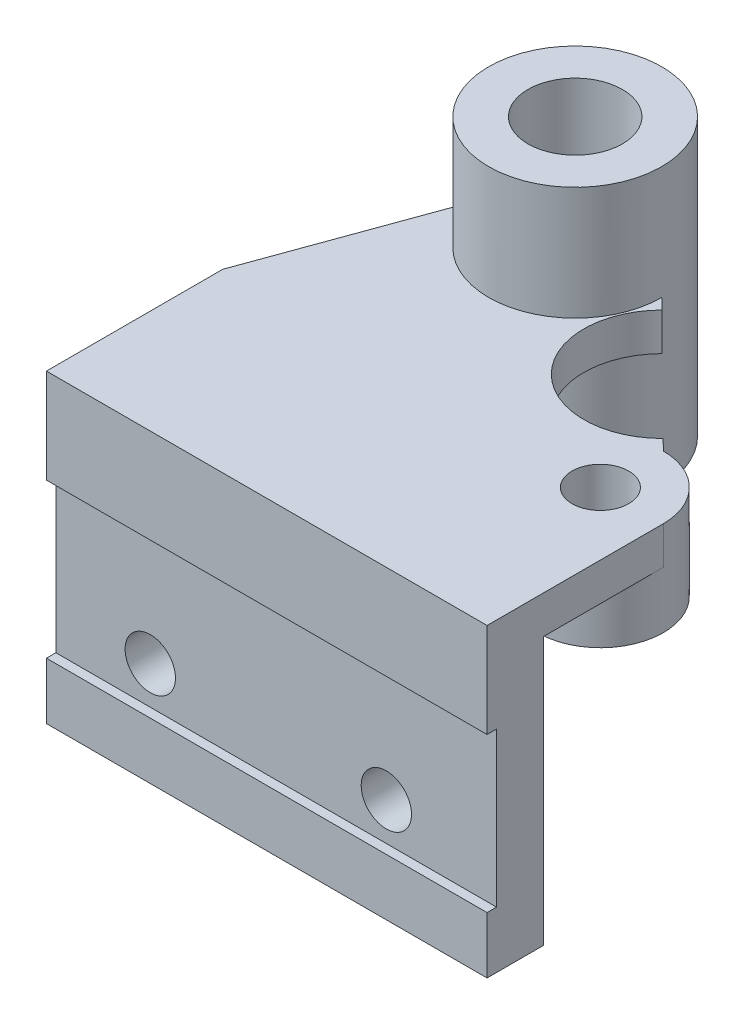
SolidWorks part; units mm, degrees
ref_plane "Front Plane" through (0, 0, 0) normal (0, 0, 1) x (1, 0, 0)
ref_plane "Top Plane" through (0, 0, 0) normal (0, 1, 0) x (1, 0, 0)
ref_plane "Right Plane" through (0, 0, 0) normal (1, 0, 0) x (0, 0, -1)
sketch "Sketch1" plane through (0, 0, 0) normal (0, 0, 1) x (1, 0, 0)
  line L1 (0, 0) -> (140, 0)
  line L2 (0, 0) -> (0, -85)
  line L3 (0, -85) -> (140, -85)
  line L4 (140, 0) -> (140, -85)
  dimension "D1" = 140
  dimension "D2" = 85
extrude "Boss-Extrude1" add sketch "Sketch1" along normal blind 18
sketch "Sketch2" plane through (140, 0, 0) normal (1, 0, 0) x (0, 0, -1)
  line L0 (-18, -85) -> (-18, 0) construction
  line L1 (-18, -18) -> (-15, -18)
  line L2 (-18, -18) -> (-18, -67)
  line L3 (-18, -67) -> (-15, -67)
  line L4 (-15, -18) -> (-15, -67)
  line L5 (-18, 0) -> (0, 0) construction
  dimension "D1" = 18
  dimension "D2" = 3
  dimension "D3" = 18
extrude "Cut-Extrude1" cut sketch "Sketch2" against normal blind 220
sketch "Sketch3" plane through (0, 0, 0) normal (0, 0, -1) x (-1, 0, 0)
  line L0 (-140, -85) -> (-140, 0) construction
  line L1 (0, -85) -> (-140, -85) construction
  line L2 (0, 0) -> (0, -85) construction
  circle A0 centre (-105, -55) radius 8
  circle A1 centre (-30, -55) radius 8
  dimension "D1" = 16
  dimension "D2" = 16
  dimension "D3" = 35
  dimension "D4" = 30
  dimension "D5" = 30
  dimension "D6" = 30
extrude "Cut-Extrude4" cut sketch "Sketch3" against normal blind 30
sketch "Sketch5" plane through (140, 0, 0) normal (1, 0, 0) x (0, 0, -1)
  line L0 (-18, 0) -> (0, 0) construction
  line L1 (-18, 0) -> (38, 0)
  line L2 (-18, 0) -> (-18, 12)
  line L3 (-18, 12) -> (38, 12)
  line L4 (38, 0) -> (38, 12)
  dimension "D1" = 12
  dimension "D2" = 56
extrude "Boss-Extrude2" add sketch "Sketch5" against normal blind 140
sketch "Sketch7" plane through (0, 0, 0) normal (0, -1, 0) x (1, 0, 0)
  line L0 (0, 0) -> (140, 0) construction
  line L2 (140, 0) -> (140, -38) construction
  circle A0 centre (120, -38) radius 20
  point P6 (140, -19)
  dimension "D2" = 40
  dimension "D1" = 38
  dimension "D3" = 20
extrude "Boss-Extrude3" add sketch "Sketch7" against normal blind 12 and the other way blind 18 from offset 0
sketch "Sketch8" plane through (0, -18, 0) normal (0, -1, 0) x (-1, 0, 0)
  line L0 (-120, 18) -> (-120, 50018) construction
  line L1 (-140, 38) -> (49860, 38) construction
  arc A0 (-140, 38) -> (-100, 38) centre (-120, 38) ccw construction
  circle A3 centre (-120, 38) radius 9
  point P5 (-120, 18)
  point P11 (-120, 38)
  dimension "D1" = 18
extrude "Cut-Extrude5" cut sketch "Sketch8" against normal blind 50
sketch "Sketch10" plane through (0, 0, 0) normal (0, -1, 0) x (1, 0, 0)
  line L0 (0, 0) -> (140, 0) construction
  line L1 (0, 0) -> (0, -38) construction
  line L2 (0, -38) -> (22.5, -100)
  line L3 (77.5, -100) -> (120, -58)
  line L4 (0, -38) -> (100, -38)
  arc A0 (77.5, -100) -> (22.5, -100) centre (50, -100) ccw
  circle A1 centre (120, -38) radius 20 construction
  arc A2 (100, -38) -> (120, -58) centre (120, -38) ccw
  dimension "D1" = 55
  dimension "D2" = 100
  dimension "D3" = 50
extrude "Boss-Extrude4" add sketch "Sketch10" against normal blind 12
sketch "Sketch11" plane through (0, 12, 0) normal (0, 1, 0) x (1, 0, 0)
  line L0 (50, 72.5) -> (50, 100) construction
  arc A0 (22.5, 100) -> (77.5, 100) centre (50, 100) ccw construction
  circle A1 centre (50, 100) radius 27.5
extrude "Boss-Extrude6" add sketch "Sketch11" along normal blind 36 and the other way blind 52
sketch "Sketch12" plane through (0, -40, 0) normal (0, -1, 0) x (1, 0, 0)
  line L0 (50, -72.5) -> (50, -127.5) construction
  arc A0 (77.5, -100) -> (22.5, -100) centre (50, -100) ccw construction
  circle A1 centre (50, -100) radius 27.5 construction
  circle A2 centre (50, -100) radius 15
  dimension "D1" = 30
extrude "Cut-Extrude6" cut sketch "Sketch12" against normal blind 109
sketch "Sketch14" plane through (0, 12, 0) normal (0, 1, 0) x (1, 0, 0)
  line L0 (98.75, 79) -> (35244.2706, 35642.9197) construction
  line L1 (77.5, 100) -> (120, 58) construction
  line L2 (80.968, 96.5728) -> (116.532, 61.4272)
  arc A0 (80.968, 96.5728) -> (116.532, 61.4272) centre (98.75, 79) ccw
  point P4 (98.75, 79)
  point P6 (0, 0)
  point P9 (80.968, 96.5728)
  point P10 (119.7327, 58.2641)
  dimension "D1" = 50
extrude "Cut-Extrude11" cut sketch "Sketch14" against normal blind 12
